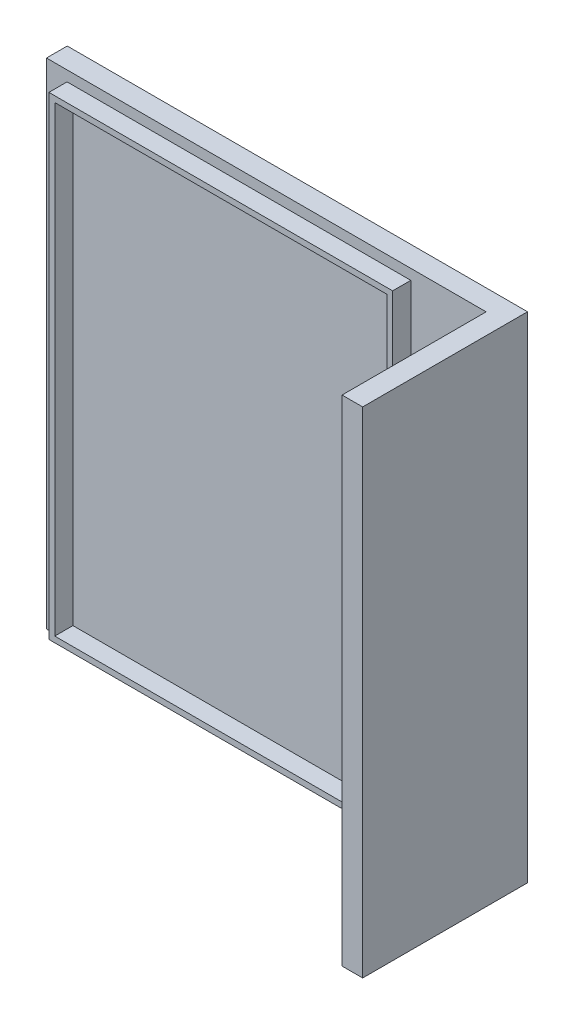
SolidWorks part; units mm, degrees
ref_plane "Front Plane" through (0, 0, 0) normal (0, 0, 1) x (1, 0, 0)
ref_plane "Top Plane" through (0, 0, 0) normal (0, 1, 0) x (1, 0, 0)
ref_plane "Right Plane" through (0, 0, 0) normal (1, 0, 0) x (0, 0, -1)
sketch "Sketch1" plane through (0, 0, 0) normal (0, 0, 1) x (1, 0, 0)
  line L1 (-16.9354, -19.05) -> (16.9354, -19.05)
  line L2 (-16.9354, -19.05) -> (-16.9354, 19.05)
  line L3 (-16.9354, 19.05) -> (16.9354, 19.05)
  line L4 (16.9354, -19.05) -> (16.9354, 19.05)
  line L5 (-16.9354, -19.05) -> (16.9354, 19.05) construction
  line L6 (-16.9354, 19.05) -> (16.9354, -19.05) construction
  point P0 (0, 0)
  dimension "D1" = 33.8709
  dimension "D2" = 38.1
extrude "Boss-Extrude1" add sketch "Sketch1" along normal blind 1.6
sketch "Sketch2" plane through (0, 0, 1.6) normal (0, 0, 1) x (1, 0, 0)
  line L1 (-15.3479, 18.2499) -> (11.1316, 18.2499)
  line L2 (-15.3479, 18.2499) -> (-15.3479, -18.2499)
  line L3 (-15.3479, -18.2499) -> (11.1316, -18.2499)
  line L4 (11.1316, 18.2499) -> (11.1316, -18.2499)
  line L5 (11.1316, 0) -> (-15.1193, 0) construction
  line L6 (16.9354, 0) -> (-16.383, 0) construction
  line L7 (16.9354, -19.05) -> (16.9354, 19.05) construction
  line L8 (-14.8979, 17.7999) -> (-14.8979, -17.7999)
  line L9 (-14.8979, -17.7999) -> (10.6816, -17.7999)
  line L10 (10.6816, 17.7999) -> (10.6816, -17.7999)
  line L11 (-14.8979, 17.7999) -> (10.6816, 17.7999)
  line L12 (-16.9354, 19.05) -> (-16.9354, -19.05) construction
  dimension "D1" = 26.4795
  dimension "D2" = 36.4998
  dimension "D4" = 1.5875
  dimension "D3" = 0.45
extrude "Boss-Extrude2" add sketch "Sketch2" along normal blind 1.4
sketch "Sketch3" plane through (16.9354, 0, 0) normal (1, 0, 0) x (0, 0, -1)
  line L0 (-1.6, 19.05) -> (0, 19.05) construction
  line L1 (0, -19.05) -> (-12.7, -19.05)
  line L2 (0, -19.05) -> (0, 19.05)
  line L3 (0, 19.05) -> (-12.7, 19.05)
  line L4 (-12.7, -19.05) -> (-12.7, 19.05)
  dimension "D1" = 12.7
extrude "Boss-Extrude3" add sketch "Sketch3" along normal blind 1.5875
